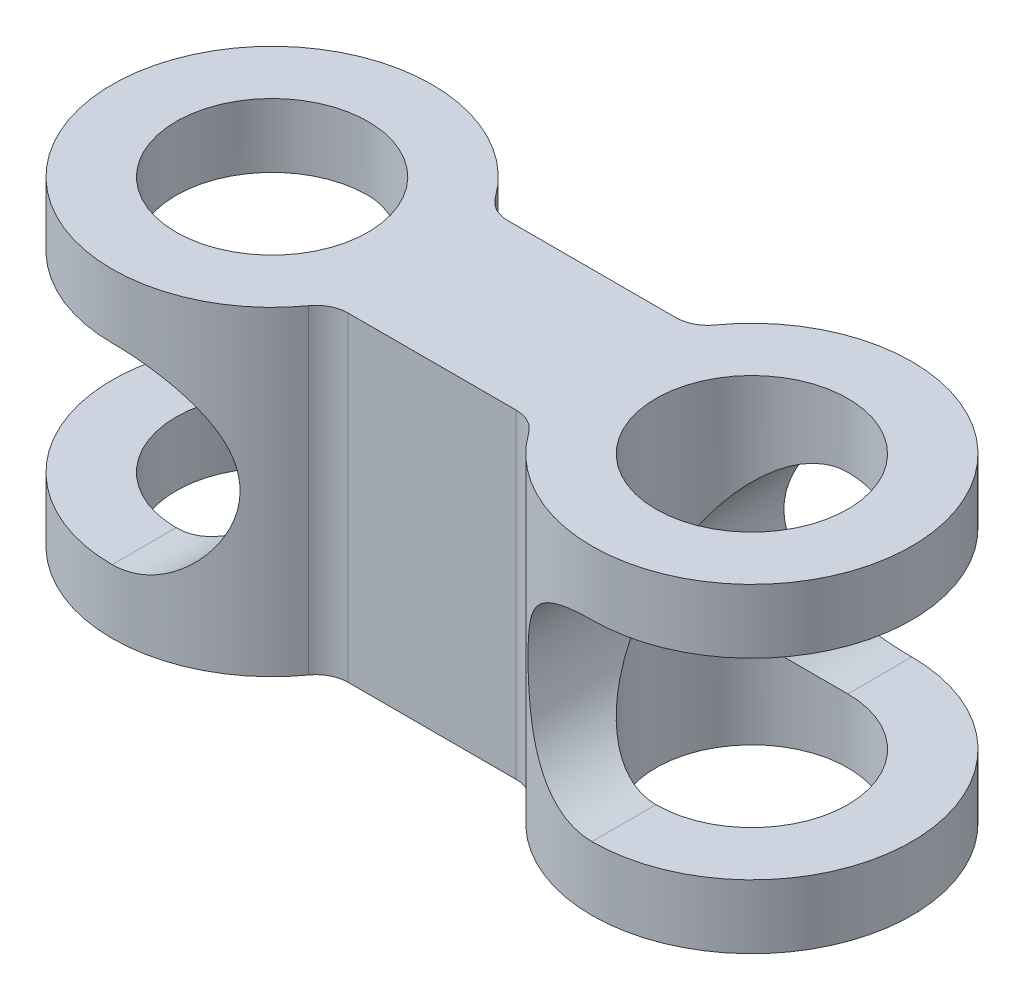
SolidWorks part; units mm, degrees
ref_plane "Front Plane" through (0, 0, 0) normal (0, 0, 1) x (1, 0, 0)
ref_plane "Top Plane" through (0, 0, 0) normal (0, 1, 0) x (1, 0, 0)
ref_plane "Right Plane" through (0, 0, 0) normal (1, 0, 0) x (0, 0, -1)
sketch "Sketch1" plane through (0, 0, 0) normal (0, 1, 0) x (1, 0, 0)
  line L1 (0, 2.5) -> (7.5, 2.5)
  line L2 (0, 2.5) -> (0, -2.5)
  line L3 (0, -2.5) -> (7.5, -2.5)
  line L4 (7.5, 2.5) -> (7.5, -2.5)
  dimension "D1" = 5
  dimension "D2" = 7.5
extrude "Boss-Extrude1" add sketch "Sketch1" along normal blind 10
sketch "Sketch2" plane through (0, 0, 0) normal (0, 1, 0) x (1, 0, 0)
  circle A0 centre (0, 0) radius 5
  dimension "D1" = 10
sketch "Sketch3" plane through (0, 0, 0) normal (0, 1, 0) x (1, 0, 0)
  circle A0 centre (0, 0) radius 3
  dimension "D1" = 6
extrude "Boss-Extrude2" add sketch "Sketch2" along normal up to surface (10 mm away) up to face at (3.75, 10, 0)
extrude "Cut-Extrude1" cut sketch "Sketch3" along normal up to next
sketch "Sketch4" plane through (0, 0, 0) normal (0, 0, 1) x (1, 0, 0)
  line L0 (0, 0) -> (0, 10) construction
  line L1 (3, 10) -> (-3, 10) construction
  line L2 (0, 8) -> (-5, 8)
  line L3 (-5, 10) -> (-5, 0) construction
  line L4 (0, 2) -> (-5, 2)
  line L5 (-5, 8) -> (-5, 2)
  arc A0 (0, 2) -> (0, 8) centre (0, 5) ccw
  dimension "D1" = 6
extrude "Cut-Extrude2" cut sketch "Sketch4" against normal through all both and the other way through all
fillet "Fillet1" radius 1 2 edges at (4.3301, 5, -2.5) (4.3301, 5, 2.5)
mirror "Mirror1" about plane through (7.5, 10, -2.5) normal (-1, 0, 0) of "Boss-Extrude1", "Cut-Extrude1", "Boss-Extrude2", "Cut-Extrude2", "Fillet1"
